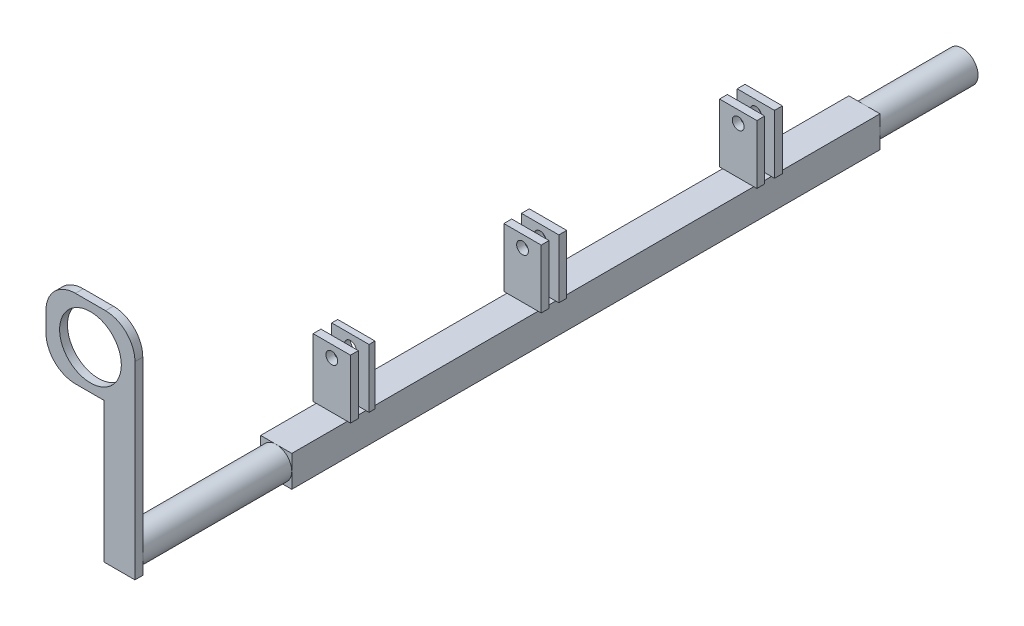
SolidWorks part; units mm, degrees
ref_plane "Alzado" through (0, 0, 0) normal (0, 0, 1) x (1, 0, 0)
ref_plane "Planta" through (0, 0, 0) normal (0, 1, 0) x (1, 0, 0)
ref_plane "Vista lateral" through (0, 0, 0) normal (1, 0, 0) x (0, 0, -1)
sketch "Croquis2" plane through (0, 0, 0) normal (0, 0, 1) x (1, 0, 0)
  line L1 (-7.94, -7.94) -> (7.94, -7.94)
  line L2 (-7.94, -7.94) -> (-7.94, 7.94)
  line L3 (-7.94, 7.94) -> (7.94, 7.94)
  line L4 (7.94, -7.94) -> (7.94, 7.94)
  line L5 (-7.94, -7.94) -> (7.94, 7.94) construction
  line L6 (-7.94, 7.94) -> (7.94, -7.94) construction
  point P0 (0, 0)
  dimension "D1" = 15.88
  dimension "D2" = 15.88
extrude "Saliente-Extruir1" add sketch "Croquis2" along normal blind 300
sketch "Croquis3" plane through (0, 0, 300) normal (0, 0, 1) x (1, 0, 0)
  circle A0 centre (0, 0) radius 7.94
  dimension "D1" = 15.88
extrude "Saliente-Extruir2" add sketch "Croquis3" along normal blind 50
sketch "Croquis5" plane through (0, 0, 0) normal (0, 0, -1) x (-1, 0, 0)
  circle A0 centre (0, 0) radius 7.94
extrude "Saliente-Extruir3" add sketch "Croquis5" along normal blind 50
sketch "Croquis6" plane through (0, 7.94, 0) normal (0, 1, 0) x (1, 0, 0)
  line L0 (7.94, -265.15) -> (-7.94, -265.15) construction
  line L1 (7.94, -300) -> (7.94, 0) construction
  line L2 (-7.94, -300) -> (-7.94, 0) construction
  line L3 (-7.94, -350) -> (7.94, -350) construction
  line L4 (0, -265.15) -> (0, -269.65) construction
  line L5 (9.525, -267.65) -> (-9.525, -267.65)
  line L6 (9.525, -267.65) -> (9.525, -271.65)
  line L7 (9.525, -271.65) -> (-9.525, -271.65)
  line L8 (-9.525, -267.65) -> (-9.525, -271.65)
  line L9 (9.525, -267.65) -> (-9.525, -271.65) construction
  line L10 (9.525, -271.65) -> (-9.525, -267.65) construction
  line L11 (0, -265.15) -> (0, -260.65) construction
  line L12 (7.94, -167.88) -> (-7.94, -167.88) construction
  line L13 (9.525, -262.1762) -> (-9.525, -262.1762)
  line L14 (9.525, -262.1762) -> (9.525, -259.1238)
  line L15 (9.525, -259.1238) -> (-9.525, -259.1238)
  line L16 (-9.525, -262.1762) -> (-9.525, -259.1238)
  line L17 (9.525, -262.1762) -> (-9.525, -259.1238) construction
  line L18 (9.525, -259.1238) -> (-9.525, -262.1762) construction
  line L19 (0, -167.88) -> (0, -172.38) construction
  line L20 (0, -167.88) -> (0, -163.38) construction
  line L21 (7.94, -57.88) -> (-7.94, -57.88) construction
  line L22 (9.525, -170.38) -> (-9.525, -170.38)
  line L23 (9.525, -170.38) -> (9.525, -174.38)
  line L24 (9.525, -174.38) -> (-9.525, -174.38)
  line L25 (-9.525, -170.38) -> (-9.525, -174.38)
  line L26 (9.525, -170.38) -> (-9.525, -174.38) construction
  line L27 (9.525, -174.38) -> (-9.525, -170.38) construction
  line L28 (9.525, -165.38) -> (-9.525, -165.38)
  line L29 (9.525, -165.38) -> (9.525, -161.38)
  line L30 (9.525, -161.38) -> (-9.525, -161.38)
  line L31 (-9.525, -165.38) -> (-9.525, -161.38)
  line L32 (9.525, -165.38) -> (-9.525, -161.38) construction
  line L33 (9.525, -161.38) -> (-9.525, -165.38) construction
  line L34 (0, -57.88) -> (0, -62.38) construction
  line L35 (0, -57.88) -> (0, -53.38) construction
  line L37 (9.525, -60.38) -> (-9.525, -60.38)
  line L38 (9.525, -60.38) -> (9.525, -64.38)
  line L39 (9.525, -64.38) -> (-9.525, -64.38)
  line L40 (-9.525, -60.38) -> (-9.525, -64.38)
  line L41 (9.525, -60.38) -> (-9.525, -64.38) construction
  line L42 (9.525, -64.38) -> (-9.525, -60.38) construction
  line L43 (-9.525, -51.38) -> (9.525, -51.38)
  line L44 (-9.525, -51.38) -> (-9.525, -55.38)
  line L45 (-9.525, -55.38) -> (9.525, -55.38)
  line L46 (9.525, -51.38) -> (9.525, -55.38)
  line L47 (-9.525, -51.38) -> (9.525, -55.38) construction
  line L48 (-9.525, -55.38) -> (9.525, -51.38) construction
  point P8 (0, -269.65)
  dimension "D1" = 84.85
  dimension "D2" = 19.05
  dimension "D3" = 4
  dimension "D4" = 4.5
  dimension "D5" = 19.05
  dimension "D6" = 4.5
  dimension "D7" = 182.12
  dimension "D8" = 4.5
  dimension "D9" = 4.5
  dimension "D10" = 4
  dimension "D11" = 4
  dimension "D12" = 292.12
  dimension "D13" = 4.5
  dimension "D14" = 4.5
  dimension "D15" = 4
  dimension "D16" = 4
extrude "Saliente-Extruir4" add sketch "Croquis6" along normal blind 30
sketch "Croquis7" plane through (0, 0, 51.38) normal (0, 0, -1) x (-1, 0, 0)
  line L0 (-9.525, 37.94) -> (9.525, 37.94) construction
  circle A0 centre (0, 31.94) radius 3
  dimension "D1" = 6
  dimension "D2" = 6
extrude "Cortar-Extruir1" cut sketch "Croquis7" against normal up to surface (220.27 mm away) up to face at (0, 17.94, 271.65)
sketch "Croquis8" plane through (0, 0, 350) normal (0, 0, 1) x (1, 0, 0)
  circle A0 centre (0, 0) radius 7.94
extrude "Saliente-Extruir5" add sketch "Croquis8" along normal blind 30
sketch "Croquis9" plane through (0, 0, 380) normal (0, 0, 1) x (1, 0, 0)
  line L0 (-7.94, 7.94) -> (-7.94, 27.0492)
  line L1 (-7.94, -7.94) -> (7.94, -7.94)
  line L2 (-7.94, -7.94) -> (-7.94, 7.94)
  line L4 (7.94, -7.94) -> (7.94, 7.94)
  line L5 (-7.94, -7.94) -> (7.94, 7.94) construction
  line L6 (-7.94, 7.94) -> (7.94, -7.94) construction
  line L7 (-7.94, 27.0492) -> (-7.94, 63.4654)
  line L9 (7.94, 63.4654) -> (7.94, 7.94)
  line L11 (-7.94, 63.4654) -> (-22.4193, 63.4654)
  line L12 (7.94, 63.4654) -> (7.94, 88.4785)
  line L13 (-7.06, 103.4785) -> (-22.4193, 103.4785)
  line L14 (-37.4193, 78.4654) -> (-37.4193, 88.4785)
  arc A0 (7.94, 88.4785) -> (-7.06, 103.4785) centre (-7.06, 88.4785) ccw
  arc A1 (-22.4193, 103.4785) -> (-37.4193, 88.4785) centre (-22.4193, 88.4785) ccw
  arc A2 (-22.4193, 63.4654) -> (-37.4193, 78.4654) centre (-22.4193, 78.4654) cw
  circle A3 centre (-14.7396, 83.4719) radius 15.7357
  point P0 (0, 0)
  dimension "D1" = 15
extrude "Saliente-Extruir6" add sketch "Croquis9" against normal blind 4
